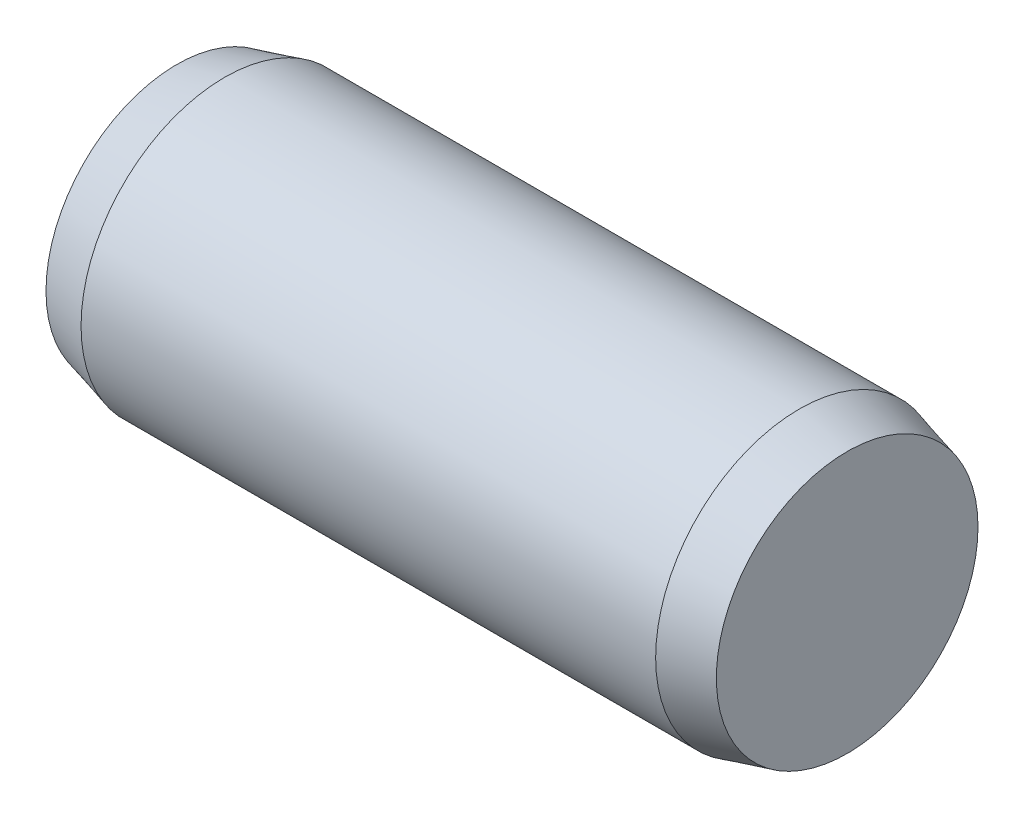
SolidWorks part; units mm, degrees
ref_plane "Front Plane" through (0, 0, 0) normal (0, 0, 1) x (1, 0, 0)
ref_plane "Top Plane" through (0, 0, 0) normal (0, 1, 0) x (1, 0, 0)
ref_plane "Right Plane" through (0, 0, 0) normal (1, 0, 0) x (0, 0, -1)
sketch "Sketch1" plane through (0, 0, 0) normal (0, 0, 1) x (1, 0, 0)
  line L0 (-3, 0) -> (3, 0) construction
  line L1 (3, 1.5) -> (3, -1.5) construction
  line L2 (-3, 1.5) -> (-3, -1.5) construction
  line L3 (3.5, 1.5) -> (3.5, -1.5) construction
  line L4 (-3.5, 1.5) -> (-3.5, -1.5) construction
  line L5 (-3, 0) -> (-3.5, 0) construction
  line L6 (3, 0) -> (3.5, 0) construction
  dimension "Dia" = 3
  dimension "C" = 0.5
  dimension "D1" = 0.5
  dimension "Length" = 7
sketch "Sketch2" plane through (0, 0, 0) normal (1, 0, 0) x (0, 0, -1)
  circle A0 centre (0, 0) radius 1.5
extrude "Extrude1" add sketch "Sketch2" against normal up to vertex (3 mm away) and the other way up to vertex (3 mm away) up to point (-3, 1.5, 0) other way up to point (3, 1.5, 0)
sketch "Sketch3" plane through (3, 0, 0) normal (1, 0, 0) x (0, 0, -1)
  circle A1 centre (0, 0) radius 1.5
  circle A2 centre (0, 0) radius 1.5
  dimension "D1" = 0
extrude "Extrude2" add sketch "Sketch3" along normal up to vertex (0.5 mm away) draft 15 up to point (3.5, 0, 0)
sketch "Sketch4" plane through (-3, 0, 0) normal (-1, 0, 0) x (0, 0, 1)
  circle A1 centre (0, 0) radius 1.5
  circle A2 centre (0, 0) radius 1.5
  dimension "D1" = 0
extrude "Extrude3" add sketch "Sketch4" along normal up to vertex (0.5 mm away) draft 15 up to point (-3.5, 0, 0)
equation "\"D1@Sketch1\" = \"C@Sketch1\""
